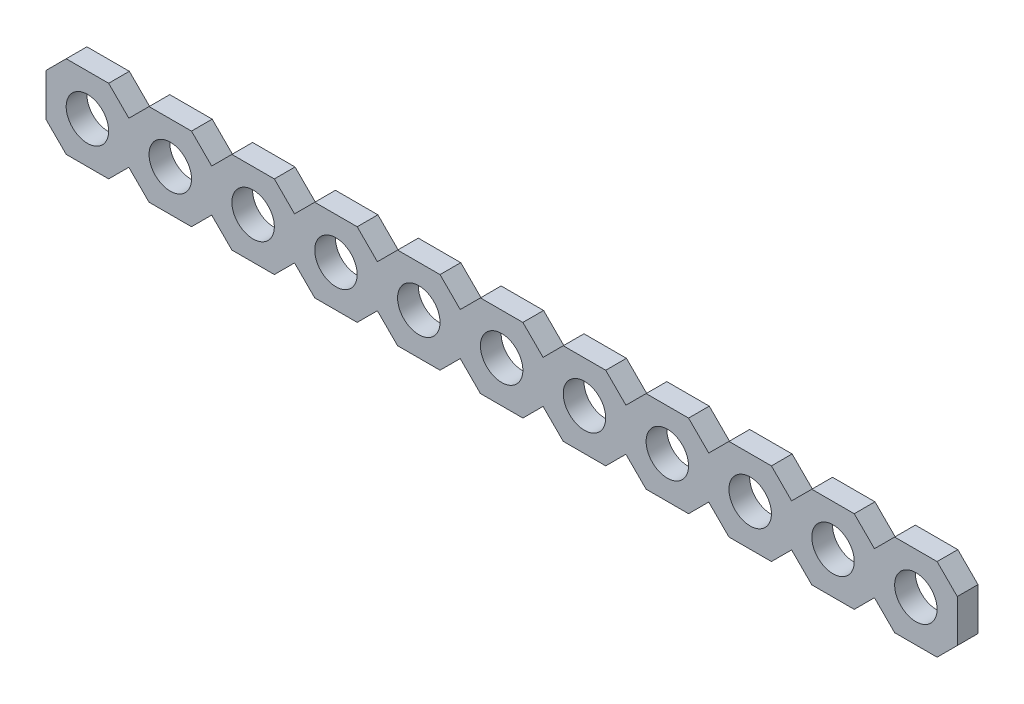
SolidWorks part; units mm, degrees
ref_plane "Front Plane" through (0, 0, 0) normal (0, 0, 1) x (1, 0, 0)
ref_plane "Top Plane" through (0, 0, 0) normal (0, 1, 0) x (1, 0, 0)
ref_plane "Right Plane" through (0, 0, 0) normal (1, 0, 0) x (0, 0, -1)
sketch "Sketch2" plane through (0, 0, 0) normal (0, 0, 1) x (1, 0, 0)
  line L0 (-4, -2.05) -> (-4, 2.05)
  line L1 (-2.05, 4) -> (2.05, 4)
  line L2 (-2.05, -4) -> (2.05, -4)
  line L3 (4, -2.05) -> (4, 2.05)
  line L4 (-4, 2.05) -> (-2.05, 4)
  line L5 (2.05, 4) -> (4, 2.05)
  line L6 (4, 2.05) -> (4.0161, 2.1369)
  line L7 (4, -2.05) -> (2.05, -4)
  line L8 (-2.05, -4) -> (-4, -2.05)
  circle A0 centre (0, 0) radius 2.05
extrude "Boss-Extrude1" add sketch "Sketch2" along normal blind 2 contours L8 L2 L7 L3 L5 L1 L4 L0 A0
pattern_linear "LPattern1" count 11 spacing 8 along (1, 0, 0) of "Boss-Extrude1"
